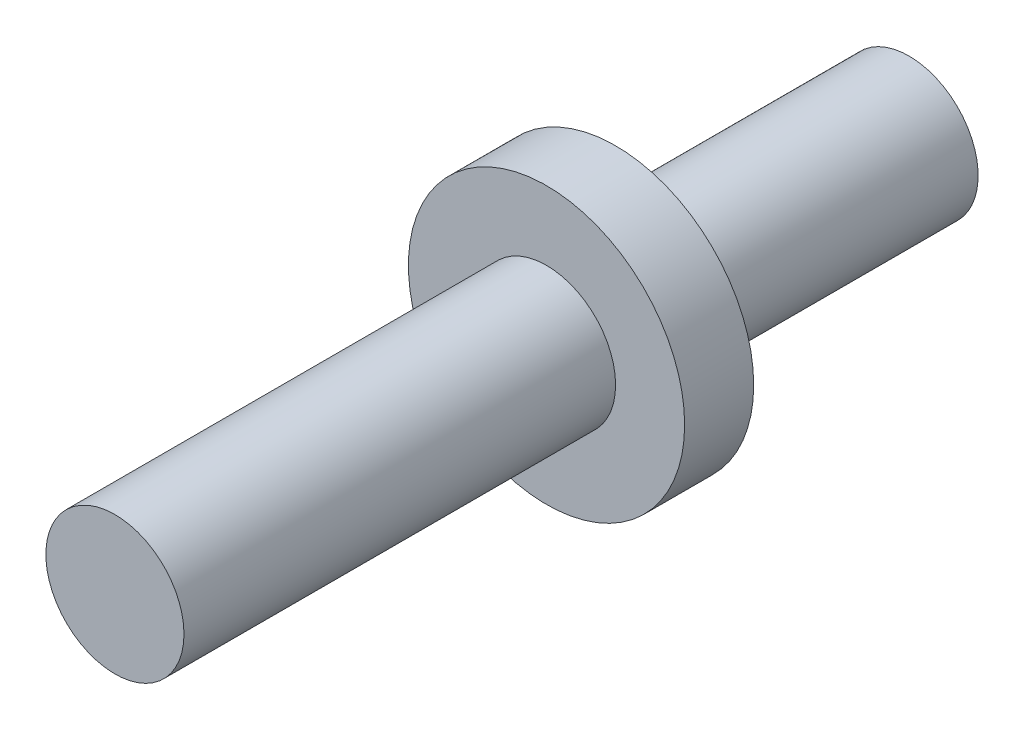
SolidWorks part; units mm, degrees
ref_plane "Plan1" through (0, 0, 0) normal (0, 0, 1) x (1, 0, 0)
ref_plane "Plan2" through (0, 0, 0) normal (0, 1, 0) x (1, 0, 0)
ref_plane "Plan3" through (0, 0, 0) normal (1, 0, 0) x (0, 0, -1)
sketch "Esquisse1" plane through (0, 0, 0) normal (0, 0, 1) x (1, 0, 0)
  circle A0 centre (0, 0) radius 16
  dimension "D1" = 32
extrude "Base-Extrusion" add sketch "Esquisse1" along normal blind 8
sketch "Esquisse2" plane through (0, 0, 8) normal (0, 0, 1) x (1, 0, 0)
  circle A0 centre (0, 0) radius 8
  circle A1 centre (0, 0) radius 16 construction
  dimension "D1" = 16
extrude "Boss.-Extru.1" add sketch "Esquisse2" along normal blind 50
sketch "Esquisse3" plane through (0, 0, 0) normal (0, 0, -1) x (-1, 0, 0)
  circle A0 centre (0, 0) radius 8
  circle A1 centre (0, 0) radius 16 construction
  dimension "D1" = 16
extrude "Boss.-Extru.2" add sketch "Esquisse3" along normal blind 34
